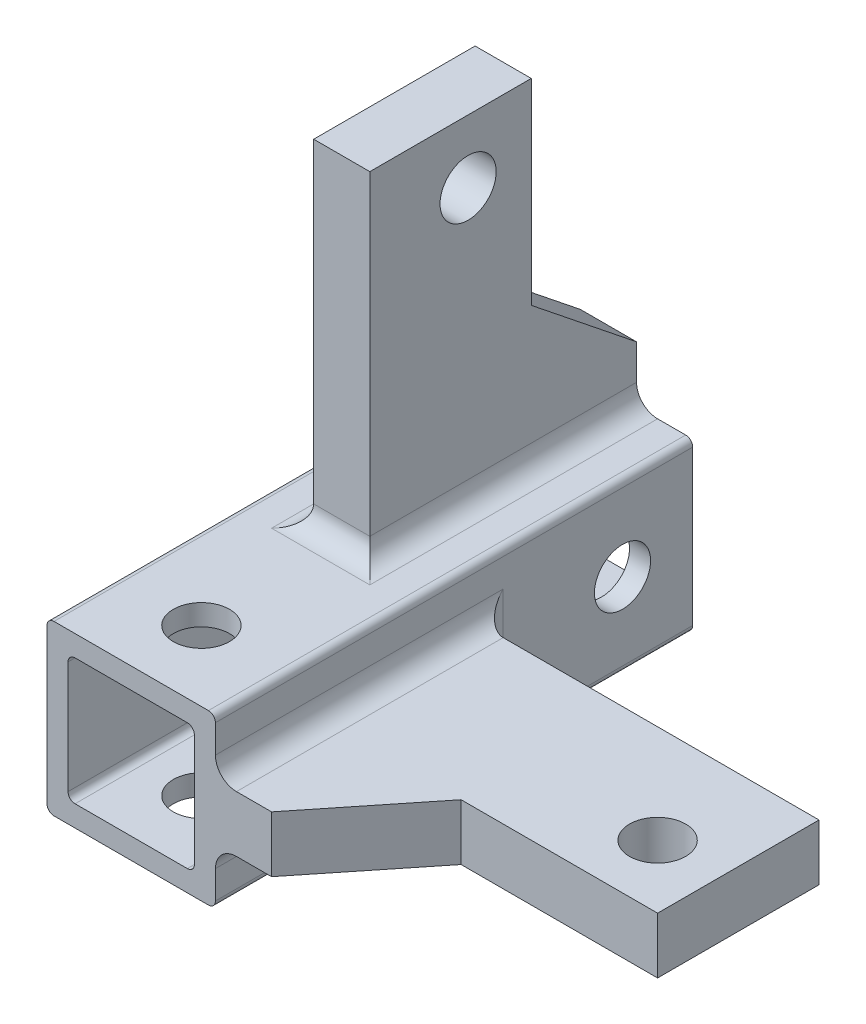
SolidWorks part; units mm, degrees
ref_plane "Front" through (0, 0, 0) normal (0, 0, 1) x (1, 0, 0)
ref_plane "Top" through (0, 0, 0) normal (0, 1, 0) x (1, 0, 0)
ref_plane "Right" through (0, 0, 0) normal (1, 0, 0) x (0, 0, -1)
sketch "Sketch1" plane through (0, 0, 0) normal (0, 0, 1) x (1, 0, 0)
  line L0 (0, 38.1) -> (0, -38.1) construction
  line L1 (-38.1, 38.1) -> (38.1, 38.1)
  line L2 (-38.1, 38.1) -> (-38.1, -38.1)
  line L3 (-38.1, -38.1) -> (38.1, -38.1)
  line L4 (38.1, 38.1) -> (38.1, -38.1)
  line L5 (-28.575, 0) -> (28.575, 0) construction
  line L6 (-28.575, 28.575) -> (28.575, 28.575)
  line L7 (-28.575, 28.575) -> (-28.575, -28.575)
  line L8 (-28.575, -28.575) -> (28.575, -28.575)
  line L9 (28.575, 28.575) -> (28.575, -28.575)
  dimension "D1" = 76.2
  dimension "D2" = 9.525
extrude "Extrude1" add sketch "Sketch1" along normal mid plane 215.9
sketch "Sketch2" plane through (0, 38.1, 0) normal (0, 1, 0) x (-1, 0, 0)
  line L1 (-38.1, 107.95) -> (38.1, 107.95) construction
  line L2 (0, 76.2) -> (0, 107.95) construction
  circle A0 centre (0, 76.2) radius 12.7
  dimension "D1" = 25.4
  dimension "D2" = 31.75
extrude "Cut-Extrude1" cut sketch "Sketch2" against normal through all
sketch "Sketch3" plane through (-38.1, 0, 0) normal (-1, 0, 0) x (0, 0, 1)
  line L0 (-76.2, 0) -> (-107.95, 0) construction
  line L1 (-107.95, 38.1) -> (-107.95, -38.1) construction
  circle A0 centre (-76.2, 0) radius 12.7
  dimension "D2" = 25.4
  dimension "D1" = 31.75
extrude "Cut-Extrude2" cut sketch "Sketch3" against normal through all
sketch "Sketch4" plane through (0, 0, 0) normal (1, 0, 0) x (0, 0, -1)
  line L0 (-12.7, 38.1) -> (107.95, 38.1)
  line L1 (-107.95, 38.1) -> (107.95, 38.1) construction
  line L2 (-12.7, 38.1) -> (-12.7, 190.5)
  line L3 (-12.7, 190.5) -> (60.325, 190.5)
  line L4 (107.95, 38.1) -> (107.95, 63.5)
  line L5 (107.95, 63.5) -> (60.325, 101.6)
  line L6 (60.325, 101.6) -> (60.325, 190.5)
  circle A1 centre (31.75, 161.925) radius 12.7
  dimension "D3" = 63.5
  dimension "D4" = 25.4
  dimension "D1" = 95.25
  dimension "D2" = 123.825
  dimension "D5" = 25.4
  dimension "D6" = 47.625
  dimension "D7" = 76.2
  dimension "D8" = 28.575
extrude "Extrude2" add sketch "Sketch4" along normal mid plane 25.4
sketch "Sketch5" plane through (0, 0, 0) normal (0, 1, 0) x (1, 0, 0)
  line L0 (38.1, 12.7) -> (38.1, -107.95)
  line L1 (38.1, 12.7) -> (190.5, 12.7)
  line L2 (190.5, 12.7) -> (190.5, -60.325)
  line L3 (38.1, -107.95) -> (63.5, -107.95)
  line L4 (63.5, -107.95) -> (101.6, -60.325)
  line L5 (101.6, -60.325) -> (190.5, -60.325)
  line L6 (38.1, -107.95) -> (38.1, 107.95) construction
  circle A1 centre (161.925, -31.75) radius 12.7
  dimension "D1" = 63.5
  dimension "D2" = 25.4
  dimension "D3" = 25.4
  dimension "D4" = 123.825
  dimension "D5" = 47.625
  dimension "D6" = 76.2
  dimension "D7" = 95.25
  dimension "D8" = 28.575
extrude "Extrude3" add sketch "Sketch5" along normal mid plane 25.4
fillet "Fillet1" radius 9.525 12 edges at (0, 38.1, 12.7) (38.1, 0, -12.7)
fillet "Fillet2" radius 3.175 10 edges at (-28.575, 28.575, 0) (-28.575, -28.575, 0) (28.575, -28.575, 0) (28.575, 28.575, 0) (-38.1, 38.1, 0) (38.1, 38.1, 0) (38.1, -38.1, 0) (-38.1, -38.1, 0)
